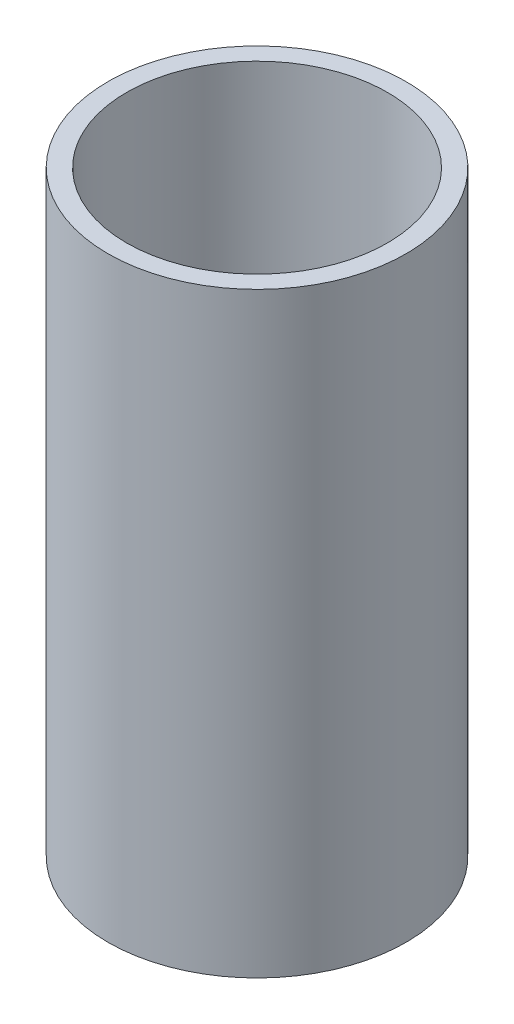
SolidWorks part; units mm, degrees
ref_plane "Front" through (0, 0, 0) normal (0, 0, 1) x (1, 0, 0)
ref_plane "Top" through (0, 0, 0) normal (0, 1, 0) x (1, 0, 0)
ref_plane "Right" through (0, 0, 0) normal (1, 0, 0) x (0, 0, -1)
sketch "Sketch1" plane through (0, 0, 0) normal (0, 1, 0) x (1, 0, 0)
  circle A0 centre (0, 0) radius 12.7
  dimension "D1" = 25.4
extrude "Boss-Extrude1" add sketch "Sketch1" along normal blind 50.8
sketch "Sketch2" plane through (0, 50.8, 0) normal (0, 1, 0) x (1, 0, 0)
  circle A0 centre (0, 0) radius 11.1125
  dimension "D1" = 22.225
extrude "Cut-Extrude1" cut sketch "Sketch2" against normal blind 44.45
